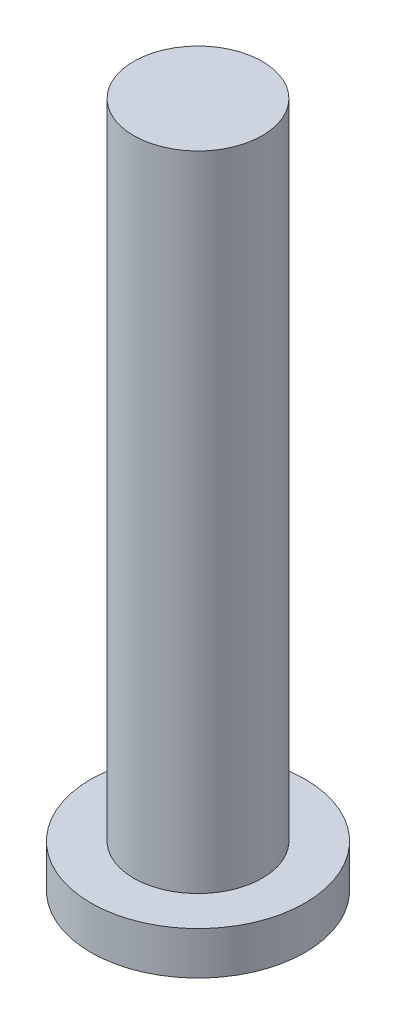
SolidWorks part; units mm, degrees
ref_plane "Plan de face" through (0, 0, 0) normal (0, 0, 1) x (1, 0, 0)
ref_plane "Plan de dessus" through (0, 0, 0) normal (0, 1, 0) x (1, 0, 0)
ref_plane "Plan de droite" through (0, 0, 0) normal (1, 0, 0) x (0, 0, -1)
sketch "Sketch1" plane through (0, 0, 0) normal (0, 1, 0) x (1, 0, 0)
  circle A0 centre (0, 0) radius 2.5
extrude "Boss-Extrude1" add sketch "Sketch1" along normal blind 1
sketch "Sketch3" plane through (0, 1, 0) normal (0, 1, 0) x (-1, 0, 0)
  circle A0 centre (0, 0) radius 1.5
extrude "Boss-Extrude2" add sketch "Sketch3" along normal blind 15
